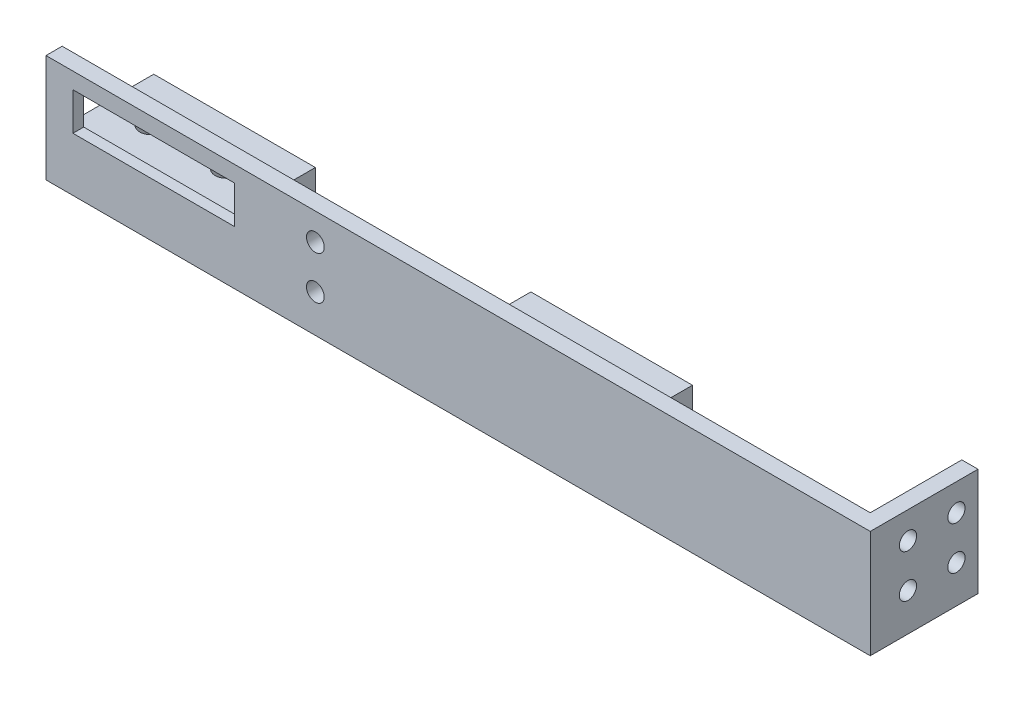
SolidWorks part; units mm, degrees
ref_plane "Front Plane" through (0, 0, 0) normal (0, 0, 1) x (1, 0, 0)
ref_plane "Top Plane" through (0, 0, 0) normal (0, 1, 0) x (1, 0, 0)
ref_plane "Right Plane" through (0, 0, 0) normal (1, 0, 0) x (0, 0, -1)
sketch "Sketch1" plane through (0, 0, 0) normal (1, 0, 0) x (0, 0, -1)
  line L1 (-88.2455, 0.4988) -> (-108.2455, 0.4988)
  line L2 (-88.2455, 0.4988) -> (-88.2455, -19.5012)
  line L3 (-88.2455, -19.5012) -> (-108.2455, -19.5012)
  line L4 (-108.2455, 0.4988) -> (-108.2455, -19.5012)
  dimension "D1" = 20
  dimension "D2" = 20
extrude "Boss-Extrude1" add sketch "Sketch1" along normal blind 3
sketch "Sketch2" plane through (0, 0, 0) normal (-1, 0, 0) x (0, 0, 1)
  line L0 (88.2455, 0.4988) -> (108.2455, 0.4988) construction
  line L1 (108.2455, -19.5012) -> (105.2455, -19.5012)
  line L2 (108.2455, -19.5012) -> (108.2455, 0.4988)
  line L3 (108.2455, 0.4988) -> (105.2455, 0.4988)
  line L4 (105.2455, -19.5012) -> (105.2455, 0.4988)
  dimension "D1" = 3
extrude "Boss-Extrude2" add sketch "Sketch2" along normal blind 150
sketch "Sketch3" plane through (0, 0, 0) normal (-1, 0, 0) x (0, 0, 1)
  line L0 (105.2455, 0.4988) -> (105.2455, -19.5012) construction
  line L1 (88.2455, -19.5012) -> (105.2455, -19.5012)
  line L2 (88.2455, -19.5012) -> (88.2455, -16.5012)
  line L3 (88.2455, -16.5012) -> (105.2455, -16.5012)
  line L4 (105.2455, -19.5012) -> (105.2455, -16.5012)
  dimension "D1" = 3
extrude "Boss-Extrude3" add sketch "Sketch3" along normal blind 150
sketch "Sketch4" plane through (3, 0, 0) normal (1, 0, 0) x (0, 0, -1)
  circle A0 centre (-101.2455, -4.5012) radius 1.6
  circle A1 centre (-92.2455, -4.5012) radius 1.6
  circle A2 centre (-92.2455, -12.5012) radius 1.6
  circle A3 centre (-101.2455, -12.5012) radius 1.6
extrude "Cut-Extrude1" cut sketch "Sketch4" against normal blind 3
sketch "Sketch5" plane through (0, -16.5012, 0) normal (0, 1, 0) x (1, 0, 0)
  line L0 (-150, -105.2455) -> (0, -105.2455) construction
  line L1 (-150, -88.2455) -> (-120, -88.2455)
  line L2 (-150, -88.2455) -> (-150, -105.2455)
  line L3 (-150, -105.2455) -> (-120, -105.2455)
  line L4 (-120, -88.2455) -> (-120, -105.2455)
  dimension "D1" = 30
extrude "Boss-Extrude4" add sketch "Sketch5" along normal blind 4
sketch "Sketch6" plane through (0, -16.5012, 0) normal (0, 1, 0) x (1, 0, 0)
  line L0 (-120, -105.2455) -> (0, -105.2455) construction
  line L1 (-80, -105.2455) -> (-50, -105.2455)
  line L2 (-80, -105.2455) -> (-80, -88.2455)
  line L3 (-80, -88.2455) -> (-50, -88.2455)
  line L4 (-50, -105.2455) -> (-50, -88.2455)
  line L5 (-120, -88.2455) -> (0, -88.2455) construction
  line L6 (-150, -88.2455) -> (-150, -105.2455) construction
  dimension "D1" = 30
  dimension "D2" = 70
extrude "Boss-Extrude5" add sketch "Sketch6" along normal blind 4
sketch "Sketch9" plane through (0, -12.5012, 0) normal (0, 1, 0) x (1, 0, 0)
  line L0 (-150, -105.2455) -> (0, -105.2455) construction
  line L1 (-80, -88.2455) -> (-80, -105.2455) construction
  line L2 (-50, -105.2455) -> (-50, -88.2455) construction
  line L3 (-120, -105.2455) -> (-120, -88.2455) construction
  line L4 (-150, -88.2455) -> (-150, -105.2455) construction
  circle A0 centre (-58, -96.7455) radius 2.05
  circle A1 centre (-72, -96.7455) radius 2.1
  circle A2 centre (-128, -96.7455) radius 2.1
  circle A3 centre (-142, -96.7455) radius 2.1
  dimension "D1" = 4.1
  dimension "D2" = 4.2
  dimension "D3" = 4.2
  dimension "D4" = 4.2
  dimension "D5" = 8.5
  dimension "D6" = 8.5
  dimension "D7" = 8
  dimension "D8" = 8
  dimension "D9" = 8.5
  dimension "D10" = 8.5
  dimension "D11" = 8
  dimension "D12" = 8
extrude "Cut-Extrude4" cut sketch "Sketch9" against normal through all
sketch "Sketch10" plane through (0, -19.5012, 0) normal (0, -1, 0) x (1, 0, 0)
  circle A0 centre (-142, 96.7455) radius 4
  circle A1 centre (-128, 96.7455) radius 4
  circle A2 centre (-72, 96.7455) radius 4
  circle A3 centre (-58, 96.7455) radius 4
  dimension "D1" = 8
  dimension "D2" = 8
  dimension "D3" = 8
  dimension "D4" = 8
extrude "Cut-Extrude5" cut sketch "Sketch10" against normal blind 2.5
sketch "Sketch11" plane through (0, 0, 108.2455) normal (0, 0, 1) x (1, 0, 0)
  line L0 (3, 0.4988) -> (-150, 0.4988) construction
  line L1 (-145, -2.5012) -> (-115, -2.5012)
  line L2 (-145, -2.5012) -> (-145, -9.5012)
  line L3 (-145, -9.5012) -> (-115, -9.5012)
  line L4 (-115, -2.5012) -> (-115, -9.5012)
  line L5 (-150, -19.5012) -> (-150, 0.4988) construction
  dimension "D1" = 7
  dimension "D2" = 3
  dimension "D3" = 5
  dimension "D4" = 30
extrude "Cut-Extrude6" cut sketch "Sketch11" against normal blind 3
chamfer "Chamfer2" distance 1 angle 45 4 edges at (-145, -6.0012, 105.2455) (-130, -9.5012, 105.2455) (-115, -6.0012, 105.2455) (-130, -2.5012, 105.2455)
chamfer "Chamfer3" distance 3 angle 45 2 edges at (-100, -16.5012, 105.2455) (-25, -16.5012, 105.2455)
sketch "Sketch12" plane through (0, -16.5012, 0) normal (0, 1, 0) x (1, 0, 0)
  line L0 (-150, -105.2455) -> (0, -105.2455) construction
  line L1 (-120, -88.2455) -> (-116.9, -88.2455)
  line L2 (-120, -88.2455) -> (-120, -105.2455)
  line L3 (-120, -105.2455) -> (-116.9, -105.2455)
  line L4 (-116.9, -88.2455) -> (-116.9, -105.2455)
  line L6 (-80, -88.2455) -> (-83.1, -88.2455)
  line L7 (-80, -88.2455) -> (-80, -105.2455)
  line L8 (-80, -105.2455) -> (-83.1, -105.2455)
  line L9 (-83.1, -88.2455) -> (-83.1, -105.2455)
  line L10 (-50, -88.2455) -> (-46.9, -88.2455)
  line L11 (-50, -88.2455) -> (-50, -105.2455)
  line L12 (-50, -105.2455) -> (-46.9, -105.2455)
  line L13 (-46.9, -88.2455) -> (-46.9, -105.2455)
  dimension "D1" = 3.1
  dimension "D2" = 3.1
  dimension "D3" = 3.1
extrude "Cut-Extrude7" cut sketch "Sketch12" along normal blind 3
sketch "Sketch13" plane through (0, 0, 105.2455) normal (0, 0, -1) x (-1, 0, 0)
  line L0 (150, 0.4988) -> (0, 0.4988) construction
  line L1 (115, -2.5012) -> (115, -9.5012) construction
  circle A0 centre (100, -4.5012) radius 1.65
  circle A1 centre (100, -12.5012) radius 1.65
  dimension "D1" = 3.3
  dimension "D2" = 3.3
  dimension "D3" = 5
  dimension "D4" = 13
  dimension "D5" = 15
  dimension "D6" = 15
extrude "Cut-Extrude8" cut sketch "Sketch13" against normal up to surface (3 mm away) up to face at (-130, -6.0012, 108.2455)
sketch "Sketch14" plane through (0, 0, 105.2455) normal (0, 0, -1) x (-1, 0, 0)
  circle A0 centre (100, -12.5012) radius 3
  dimension "D1" = 6
extrude "Cut-Extrude9" cut sketch "Sketch14" along normal blind 6
